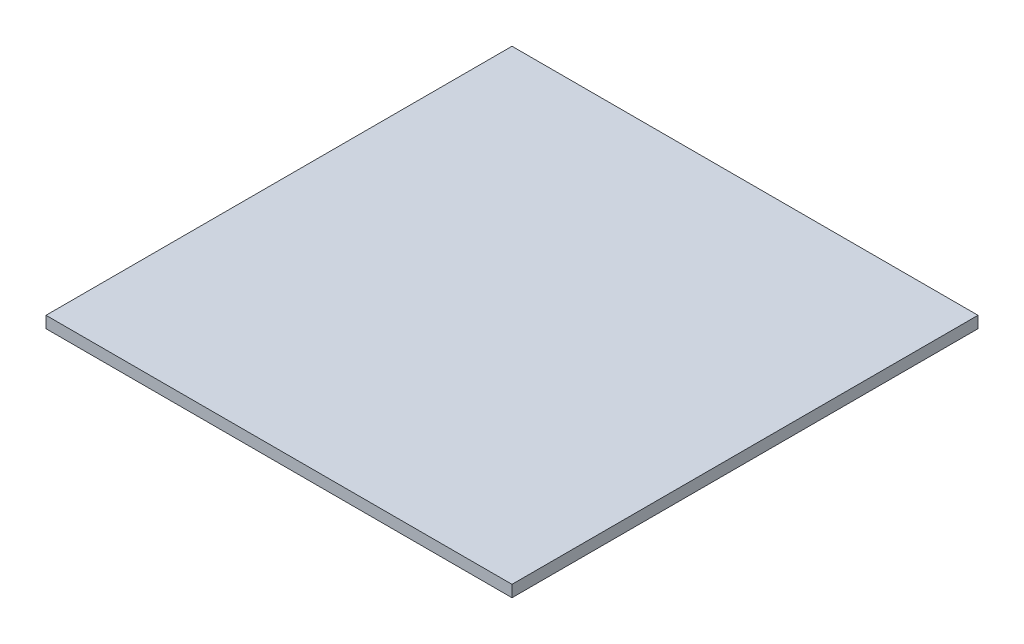
SolidWorks part; units mm, degrees
ref_plane "Front Plane" through (0, 0, 0) normal (0, 0, 1) x (1, 0, 0)
ref_plane "Top Plane" through (0, 0, 0) normal (0, 1, 0) x (1, 0, 0)
ref_plane "Right Plane" through (0, 0, 0) normal (1, 0, 0) x (0, 0, -1)
sketch "Sketch1" plane through (0, 0, 0) normal (0, 1, 0) x (1, 0, 0)
  line L1 (-50, 50) -> (50, 50)
  line L2 (-50, 50) -> (-50, -50)
  line L3 (-50, -50) -> (50, -50)
  line L4 (50, 50) -> (50, -50)
  line L5 (-50, 50) -> (50, -50) construction
  line L6 (-50, -50) -> (50, 50) construction
  point P0 (0, 0)
  dimension "D1" = 100
  dimension "D2" = 100
extrude "Boss-Extrude1" add sketch "Sketch1" along normal blind 2.5
